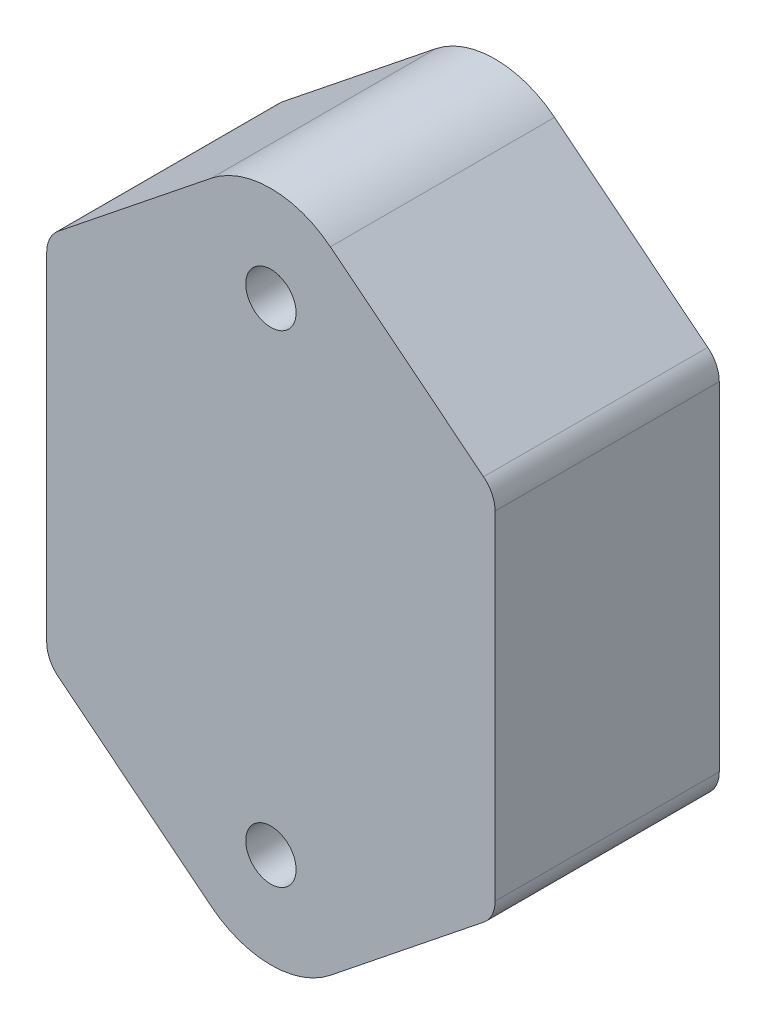
SolidWorks part; units mm, degrees
ref_plane "Front Plane" through (0, 0, 0) normal (0, 0, 1) x (1, 0, 0)
ref_plane "Top Plane" through (0, 0, 0) normal (0, 1, 0) x (1, 0, 0)
ref_plane "Right Plane" through (0, 0, 0) normal (1, 0, 0) x (0, 0, -1)
sketch "Sketch1" plane through (0, 0, 0) normal (0, 0, 1) x (1, 0, 0)
  line L0 (-2.54, 0) -> (-2.54, 27.94)
  line L1 (34.544, 27.94) -> (34.544, 0)
  line L2 (33.5906, -1.9835) -> (20.9203, -12.118)
  line L3 (11.0837, -12.118) -> (-1.5866, -1.9835)
  line L4 (-1.5866, 29.9235) -> (11.0837, 40.058)
  line L5 (20.9203, 40.058) -> (33.5906, 29.9235)
  arc A0 (11.0837, 40.058) -> (20.9203, 40.058) centre (16.002, 33.909) cw
  circle A1 centre (16.002, 33.909) radius 2.0828
  arc A2 (20.9203, -12.118) -> (11.0837, -12.118) centre (16.002, -5.969) cw
  circle A3 centre (16.002, -5.969) radius 2.0828
  arc A4 (-2.54, 0) -> (-1.5866, -1.9835) centre (0, 0) ccw
  arc A5 (34.544, 0) -> (33.5906, -1.9835) centre (32.004, 0) cw
  arc A6 (33.5906, 29.9235) -> (34.544, 27.94) centre (32.004, 27.94) cw
  arc A7 (-2.54, 27.94) -> (-1.5866, 29.9235) centre (0, 27.94) cw
  point P15 (0, 0)
  point P22 (16.002, 41.783)
  point P23 (16.002, -13.843)
  point P26 (34.544, 13.97)
  dimension "D1" = 39.878
  dimension "D2" = 4.1656
  dimension "D3" = 2.54
  dimension "D5" = 55.626
  dimension "D4" = 37.084
  dimension "D6" = 19.939
  dimension "D7" = 27.94
extrude "Boss-Extrude1" add sketch "Sketch1" along normal blind 18.542
